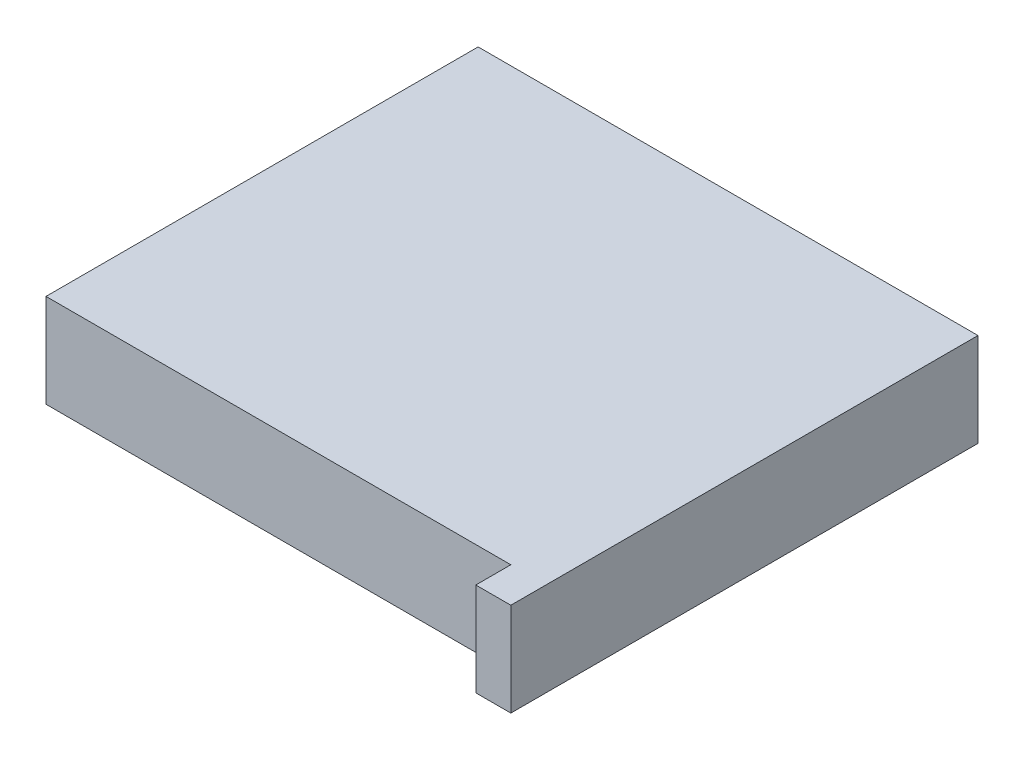
SolidWorks part; units mm, degrees
material "Cast Alloy Steel"
ref_plane "Front Plane" through (0, 0, 0) normal (0, 0, 1) x (1, 0, 0)
ref_plane "Top Plane" through (0, 0, 0) normal (0, 1, 0) x (1, 0, 0)
ref_plane "Right Plane" through (0, 0, 0) normal (1, 0, 0) x (0, 0, -1)
sketch "Sketch1" plane through (0, 0, 0) normal (0, 1, 0) x (1, 0, 0)
  line L1 (0, 0) -> (39.8, 0)
  line L2 (0, 0) -> (0, 37)
  line L3 (0, 37) -> (42.8, 37)
  line L4 (42.8, 0) -> (42.8, 37)
  line L6 (42.8, 0) -> (42.8, -3)
  line L7 (42.8, -3) -> (39.8, -3)
  line L8 (39.8, 0) -> (39.8, -3)
  dimension "D1" = 37
  dimension "D2" = 42.8
  dimension "D3" = 3
  dimension "D4" = 90
  dimension "D5" = 3
extrude "Boss-Extrude1" add sketch "Sketch1" along normal blind 8
